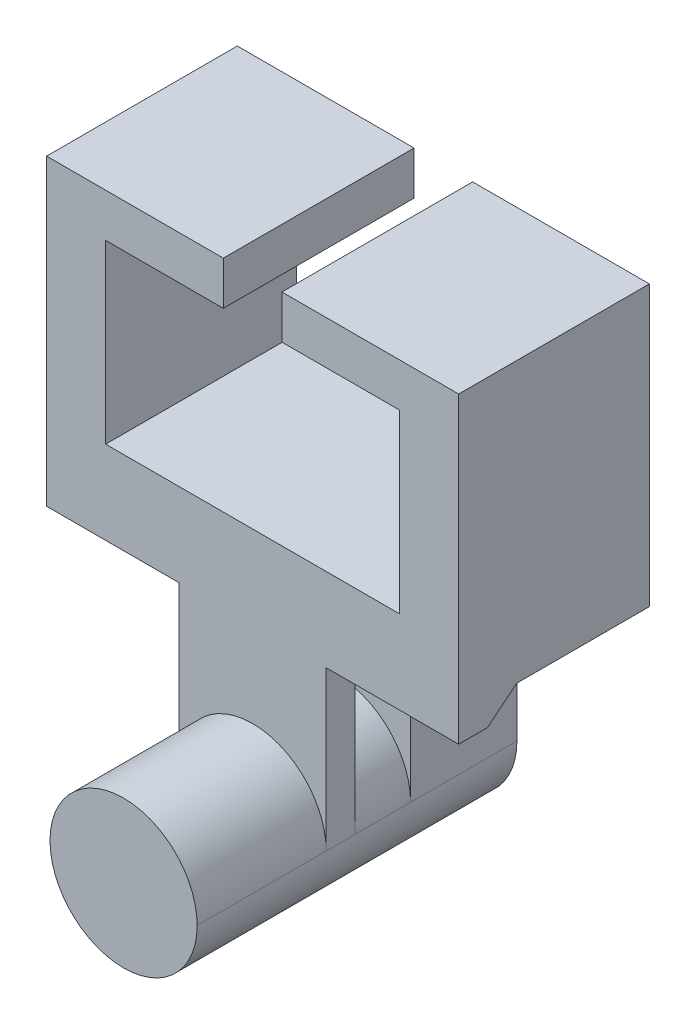
SolidWorks part; units mm, degrees
other "Markup1"
sketch "Sketch23" plane through (44.45, 98.3996, 50.8) normal (0.8427, 0.2276, 0.488) x (0.5196, -0.1064, -0.8478)
material "Ti-6Al-4VSolution treated and aged (SS)"
ref_plane "Front Plane" through (0, 0, 0) normal (0, 0, 1) x (1, 0, 0)
ref_plane "Top Plane" through (0, 0, 0) normal (0, 1, 0) x (1, 0, 0)
ref_plane "Right Plane" through (0, 0, 0) normal (1, 0, 0) x (0, 0, -1)
sketch "Sketch1" plane through (0, 0, 0) normal (0, 0, 1) x (1, 0, 0)
  circle A0 centre (0, 0) radius 15.875
  dimension "D1" = 31.75
extrude "Boss-Extrude1" add sketch "Sketch1" along normal blind 50.8
sketch "Sketch2" plane through (0, 0, 0) normal (0, 0, -1) x (-1, 0, 0)
  line L1 (-15.875, 0) -> (15.875, 0)
  line L2 (-15.875, 0) -> (-15.875, 50.8)
  line L3 (-15.875, 50.8) -> (15.875, 50.8)
  line L4 (15.875, 0) -> (15.875, 50.8)
  circle A0 centre (0, 0) radius 15.875 construction
  point P6 (0, 0)
  dimension "D1" = 50.8
  dimension "D2" = 31.75
extrude "Boss-Extrude2" add sketch "Sketch2" against normal blind 4.7625
sketch "Sketch3" plane through (0, 50.8, 0) normal (0, 1, 0) x (1, 0, 0)
  line L1 (-44.45, -22.9553) -> (44.45, -22.9553)
  line L2 (-44.45, -22.9553) -> (-44.45, 18.1928)
  line L3 (-44.45, 18.1928) -> (44.45, 18.1928)
  line L4 (44.45, -22.9553) -> (44.45, 18.1928)
  line L5 (-44.45, -22.9553) -> (44.45, 18.1928) construction
  line L6 (-44.45, 18.1928) -> (44.45, -22.9553) construction
  point P0 (0, -2.3812)
  dimension "D1" = 88.9
  dimension "D2" = 41.148
extrude "Boss-Extrude3" add sketch "Sketch3" along normal blind 41.2496
sketch "Sketch5" plane through (0, 0, 22.9553) normal (0, 0, 1) x (1, 0, 0)
  line L0 (-6.3246, 92.0496) -> (-6.3246, 90.297)
  line L1 (-44.45, 92.0496) -> (44.45, 92.0496) construction
  line L2 (-6.3246, 90.297) -> (-31.7043, 90.297)
  line L3 (-31.7043, 90.297) -> (-31.7043, 52.2224)
  line L4 (-31.7043, 52.2224) -> (31.7043, 52.2224)
  line L5 (31.7043, 52.2224) -> (31.7043, 90.297)
  line L6 (31.7043, 90.297) -> (6.3246, 90.297)
  line L7 (6.3246, 90.297) -> (6.3246, 92.0496)
  line L8 (6.3246, 92.0496) -> (-6.3246, 92.0496)
  line L9 (-44.45, 50.8) -> (44.45, 50.8) construction
  point P4 (0, 92.0496)
  point P11 (0, 52.2224)
  dimension "D1" = 38.0746
  dimension "D2" = 1.4224
  dimension "D3" = 25.3797
  dimension "D4" = 12.6492
  dimension "D5" = 38.0746
extrude "Cut-Extrude2" cut sketch "Sketch5" against normal through all
sketch "Sketch11" plane through (0, 0, 0) normal (0, 1, 0) x (1, 0, 0)
  line L1 (0, 0) -> (-15.875, 0)
  line L3 (0, -50.8) -> (-15.875, -50.8)
  line L4 (-15.875, 0) -> (-15.875, -50.8)
  line L5 (0, 0) -> (15.875, 0)
  line L7 (0, -50.8) -> (15.875, -50.8)
  line L8 (15.875, 0) -> (15.875, -50.8)
split line "Split Line2"
sketch "Sketch12" plane through (0, 50.8, 0) normal (0, -1, 0) x (1, 0, 0)
  line L0 (-44.45, 22.9553) -> (44.45, 22.9553) construction
  line L1 (-15.875, 22.9553) -> (15.875, 22.9553)
  line L2 (-15.875, 22.9553) -> (-15.875, 16.7519)
  line L3 (-15.875, 16.7519) -> (15.875, 16.7519)
  line L4 (15.875, 22.9553) -> (15.875, 16.7519)
extrude "Boss-Extrude4" add sketch "Sketch12" along normal up to next
sketch "Sketch13" plane through (0, 50.8, 0) normal (0, -1, 0) x (1, 0, 0)
  line L0 (-44.45, 22.9553) -> (-15.875, 22.9553)
  line L1 (-15.875, 22.9553) -> (-15.875, 16.7519)
  line L2 (-15.875, 16.7519) -> (15.875, 16.7519)
  line L3 (15.875, 16.7519) -> (15.875, 22.9553)
  line L4 (15.875, 22.9553) -> (44.45, 22.9553)
  line L5 (44.45, 22.9553) -> (44.45, -18.1928)
  line L6 (44.45, -18.1928) -> (-44.45, -18.1928)
  line L7 (-44.45, -18.1928) -> (-44.45, 22.9553)
  line L8 (-15.875, 0) -> (-15.875, 4.7625)
  line L9 (-15.875, 4.7625) -> (15.875, 4.7625)
  line L10 (15.875, 4.7625) -> (15.875, 0)
  line L11 (15.875, 0) -> (-15.875, 0)
extrude "Boss-Extrude5" add sketch "Sketch13" along normal blind 11.43
sketch "Sketch14" plane through (0, 92.0496, 0) normal (0, 1, 0) x (1, 0, 0)
  line L0 (-6.3246, 18.1928) -> (-6.3246, -22.9553)
  line L1 (-44.45, 18.1928) -> (-6.3246, 18.1928)
  line L2 (-44.45, 18.1928) -> (-44.45, -22.9553)
  line L3 (-44.45, -22.9553) -> (-6.3246, -22.9553)
  line L4 (44.45, 18.1928) -> (44.45, -22.9553)
  line L5 (6.3246, 18.1928) -> (6.3246, -22.9553)
  line L6 (6.3246, 18.1928) -> (6.3246, -22.9553) construction
  line L7 (6.3246, 18.1928) -> (44.45, 18.1928)
  line L8 (6.3246, -22.9553) -> (44.45, -22.9553)
extrude "Boss-Extrude6" add sketch "Sketch14" along normal blind 7.62
sketch "Sketch20" plane through (0, 0, 16.7519) normal (0, 0, -1) x (-1, 0, 0)
  line L0 (15.875, 0) -> (15.875, 39.37) construction
  line L1 (-15.875, 39.37) -> (15.875, 39.37)
  line L2 (-15.875, 39.37) -> (-15.875, 34.2397)
  line L3 (-15.875, 34.2397) -> (15.875, 34.2397)
  line L4 (15.875, 39.37) -> (15.875, 34.2397)
extrude "Boss-Extrude7" add sketch "Sketch20" along normal blind 6.35
sketch "Sketch21" plane through (15.875, 0, 0) normal (1, 0, 0) x (0, 0, -1)
  line L0 (-16.7519, 34.2397) -> (-10.4019, 39.37)
  line L1 (-10.4019, 39.37) -> (-10.4019, 34.2397)
  line L2 (-10.4019, 34.2397) -> (-16.7519, 34.2397)
extrude "Cut-Extrude3" cut sketch "Sketch21" against normal through all
sketch "Sketch22" plane through (0, 0, 0) normal (0, 0, -1) x (-1, 0, 0)
  line L1 (-15.875, 39.37) -> (15.875, 39.37)
  line L2 (-15.875, 39.37) -> (-15.875, 0)
  line L4 (15.875, 39.37) -> (15.875, 0)
  arc A0 (-15.875, 0) -> (15.875, 0) centre (0, 0) ccw
extrude "Boss-Extrude8" add sketch "Sketch22" along normal up to surface (18.1928 mm away) up to face at (0, 78.5876, -18.1928)
sketch "Sketch25" plane through (0, 39.37, 0) normal (0, -1, 0) x (1, 0, 0)
  line L1 (-15.875, 4.7625) -> (-44.45, 4.7625)
  line L2 (-15.875, 4.7625) -> (-15.875, -18.1928)
  line L3 (-15.875, -18.1928) -> (-44.45, -18.1928)
  line L4 (-44.45, 4.7625) -> (-44.45, -18.1928)
  line L5 (15.875, 4.7625) -> (44.45, 4.7625)
  line L6 (15.875, 4.7625) -> (15.875, -18.1928)
  line L7 (15.875, -18.1928) -> (44.45, -18.1928)
  line L8 (44.45, 4.7625) -> (44.45, -18.1928)
extrude "Boss-Extrude10" add sketch "Sketch25" along normal blind 6.35
sketch "Sketch26" plane through (0, 0, 4.7625) normal (0, 0, 1) x (1, 0, 0)
  line L0 (-44.45, 39.37) -> (-16.3504, 33.02)
  line L1 (-15.875, 33.02) -> (-44.45, 33.02) construction
  line L2 (15.875, 33.02) -> (44.45, 39.37)
  line L3 (-44.45, 39.37) -> (-44.45, 33.02)
  line L4 (-44.45, 33.02) -> (-16.3504, 33.02)
  line L5 (15.875, 33.02) -> (44.45, 33.02)
  line L6 (44.45, 33.02) -> (44.45, 39.37)
extrude "Cut-Extrude4" cut sketch "Sketch26" against normal through all
sketch "Sketch27" plane through (-15.875, 0, 0) normal (-1, 0, 0) x (0, 0, 1)
  line L0 (16.7519, 34.2397) -> (22.9553, 34.2397)
  line L1 (22.9553, 0) -> (22.9553, 39.37) construction
  line L2 (22.9553, 34.2397) -> (22.9553, 39.37)
  line L3 (10.4019, 39.37) -> (22.9553, 39.37) construction
  line L4 (22.9553, 39.37) -> (10.4019, 39.37)
  line L5 (10.4019, 39.37) -> (16.7519, 34.2397) construction
  line L6 (10.4019, 39.37) -> (16.7519, 34.2397)
extrude "Boss-Extrude11" add sketch "Sketch27" along normal up to surface (28.575 mm away) up to face at (-44.45, 63.4898, 2.8575)
sketch "Sketch28" plane through (15.875, 0, 0) normal (1, 0, 0) x (0, 0, -1)
  line L0 (-16.7519, 34.2397) -> (-22.9553, 34.2397)
  line L1 (-22.9553, 34.2397) -> (-22.9553, 39.37)
  line L2 (-22.9553, 39.37) -> (-10.4019, 39.37)
  line L3 (-10.4019, 39.37) -> (-16.7519, 34.2397)
extrude "Boss-Extrude12" add sketch "Sketch28" along normal up to surface (28.575 mm away) up to face at (44.45, 63.4898, 2.8575)
equation "\"D-pin\"= 1.13in"
equation "\"pin lenght\"= 2.00in"
equation "\"feature b Hight\"= 2in"
equation "\"Feathure b thickness\"= .14in"
equation "\"Brackect hight\"= 1.62in"
equation "\"brackect thickness\"= 1.62in"
equation "\"Top stem\"= 0.498in"
equation "\"flange\"= .9992in"
equation "\"lower cavity Height\"= 1.499"
